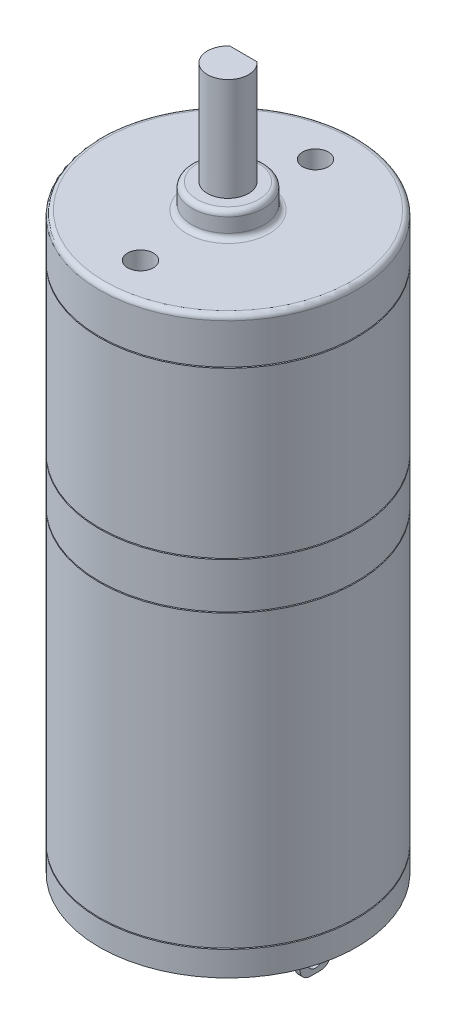
SolidWorks part; units mm, degrees
material "AISI 304"
ref_plane "Front Plane" through (0, 0, 0) normal (0, 0, 1) x (1, 0, 0)
ref_plane "Top Plane" through (0, 0, 0) normal (0, 1, 0) x (1, 0, 0)
ref_plane "Right Plane" through (0, 0, 0) normal (1, 0, 0) x (0, 0, -1)
sketch "Sketch1" plane through (0, 0, 0) normal (0, 1, 0) x (1, 0, 0)
  circle A0 centre (0, 0) radius 12.5
  dimension "D1" = 25
extrude "Boss-Extrude1" add sketch "Sketch1" along normal blind 4.4
sketch "Sketch2" plane through (0, 0, 0) normal (0, -1, 0) x (1, 0, 0)
  circle A0 centre (0, 0) radius 12.15
  dimension "D1" = 24.3
extrude "Boss-Extrude2" add sketch "Sketch2" along normal blind 0.1
sketch "Sketch3" plane through (0, -0.1, 0) normal (0, -1, 0) x (1, 0, 0)
  circle A0 centre (0, 0) radius 12.5
  dimension "D1" = 25
extrude "Boss-Extrude3" add sketch "Sketch3" along normal blind 16
sketch "Sketch4" plane through (0, -16.1, 0) normal (0, -1, 0) x (1, 0, 0)
  circle A0 centre (0, 0) radius 12.15
  dimension "D1" = 24.3
extrude "Boss-Extrude4" add sketch "Sketch4" along normal blind 0.1
sketch "Sketch5" plane through (0, -16.2, 0) normal (0, -1, 0) x (1, 0, 0)
  circle A0 centre (0, 0) radius 12.5
  dimension "D1" = 25
extrude "Boss-Extrude5" add sketch "Sketch5" along normal blind 4.4
sketch "Sketch6" plane through (0, -20.6, 0) normal (0, -1, 0) x (1, 0, 0)
  circle A0 centre (0, 0) radius 12.15
  dimension "D1" = 24.3
extrude "Boss-Extrude6" add sketch "Sketch6" along normal blind 0.1
sketch "Sketch7" plane through (0, -20.7, 0) normal (0, -1, 0) x (1, 0, 0)
  circle A0 centre (0, 0) radius 12.5
  dimension "D1" = 25
extrude "Boss-Extrude7" add sketch "Sketch7" along normal blind 28.2
sketch "Sketch8" plane through (0, -48.9, 0) normal (0, -1, 0) x (1, 0, 0)
  circle A0 centre (0, 0) radius 12.15
  dimension "D1" = 24.3
extrude "Boss-Extrude8" add sketch "Sketch8" along normal blind 0.1
sketch "Sketch9" plane through (0, -49, 0) normal (0, -1, 0) x (1, 0, 0)
  circle A0 centre (0, 0) radius 12.5
  dimension "D1" = 25
extrude "Boss-Extrude9" add sketch "Sketch9" along normal blind 2.4
sketch "Sketch10" plane through (0, -51.4, 0) normal (0, -1, 0) x (1, 0, 0)
  circle A0 centre (0, 0) radius 11.5
  dimension "D1" = 23
extrude "Cut-Extrude1" cut sketch "Sketch10" against normal blind 0.8
sketch "Sketch11" plane through (0, -50.6, 0) normal (0, -1, 0) x (1, 0, 0)
  line L0 (-16.4642, 0) -> (16.846, 0) construction
  line L1 (0, 13.4656) -> (0, -14.0496) construction
  line L2 (-8.5, 1.5) -> (-8.5, -1.5)
  line L3 (-8.5, -1.5) -> (-8, -1.5)
  line L4 (-8, -1.5) -> (-8, 1.5)
  line L5 (-8, 1.5) -> (-8.5, 1.5)
  line L6 (8, -1.5) -> (8, 1.5)
  line L7 (8.5, -1.5) -> (8, -1.5)
  line L8 (8.5, 1.5) -> (8.5, -1.5)
  line L9 (8, 1.5) -> (8.5, 1.5)
  dimension "D1" = 1.5
  dimension "D2" = 1.5
  dimension "D3" = 0.5
  dimension "D4" = 8
extrude "Boss-Extrude10" add sketch "Sketch11" along normal blind 5
sketch "Sketch12" plane through (8.5, 0, 0) normal (1, 0, 0) x (0, 0, -1)
  line L0 (0, 11.522) -> (0, -70.1892) construction
  line L1 (1.5, -55.6) -> (-1.5, -55.6) construction
  circle A0 centre (0, -54.4) radius 0.75
  point P5 (0, -54.4144)
  dimension "D1" = 1.5
  dimension "D2" = 1.2
extrude "Cut-Extrude2" cut sketch "Sketch12" against normal through all
fillet "Fillet1" radius 1 4 edges at (-8.25, -55.6, 1.5) (-8.25, -55.6, -1.5) (8.25, -55.6, -1.5) (8.25, -55.6, 1.5)
sketch "Sketch13" plane through (0, 4.4, 0) normal (0, 1, 0) x (1, 0, 0)
  line L0 (-16.1722, 0) -> (15.4085, 0) construction
  line L1 (0, 13.4431) -> (0, -13.7351) construction
  circle A0 centre (0, 8.5) radius 1.25
  circle A1 centre (0, -8.5) radius 1.25
  dimension "D1" = 2.5
  dimension "D2" = 8.5
extrude "Cut-Extrude3" cut sketch "Sketch13" against normal blind 8
cosmetic thread "Cosmetic Thread1" parameters "D2"=3
cosmetic thread "Cosmetic Thread2" parameters "D2"=3
sketch "Sketch14" plane through (0, 4.4, 0) normal (0, 1, 0) x (1, 0, 0)
  circle A0 centre (0, 0) radius 3.5
  dimension "D1" = 7
extrude "Boss-Extrude11" add sketch "Sketch14" along normal blind 2.38
sketch "Sketch15" plane through (0, 6.78, 0) normal (0, 1, 0) x (1, 0, 0)
  circle A0 centre (0, 0) radius 2
  dimension "D1" = 4
extrude "Boss-Extrude12" add sketch "Sketch15" along normal blind 10
sketch "Sketch16" plane through (0, 16.78, 0) normal (0, 1, 0) x (1, 0, 0)
  line L0 (-14.1956, 0) -> (13.3196, 0) construction
  line L1 (-1.3229, 1.5) -> (1.3229, 1.5)
  line L3 (-14.1956, 1.5) -> (13.3196, 1.5) construction
  arc A0 (1.3229, 1.5) -> (-1.3229, 1.5) centre (0, 0) ccw
  dimension "D1" = 4
  dimension "D2" = 1.5
extrude "Cut-Extrude4" cut sketch "Sketch16" against normal blind 8
fillet "Fillet2" radius 0.5 3 edges at (0, 4.4, 3.5) (0, 6.78, 3.5) (0, 4.4, 12.5)
